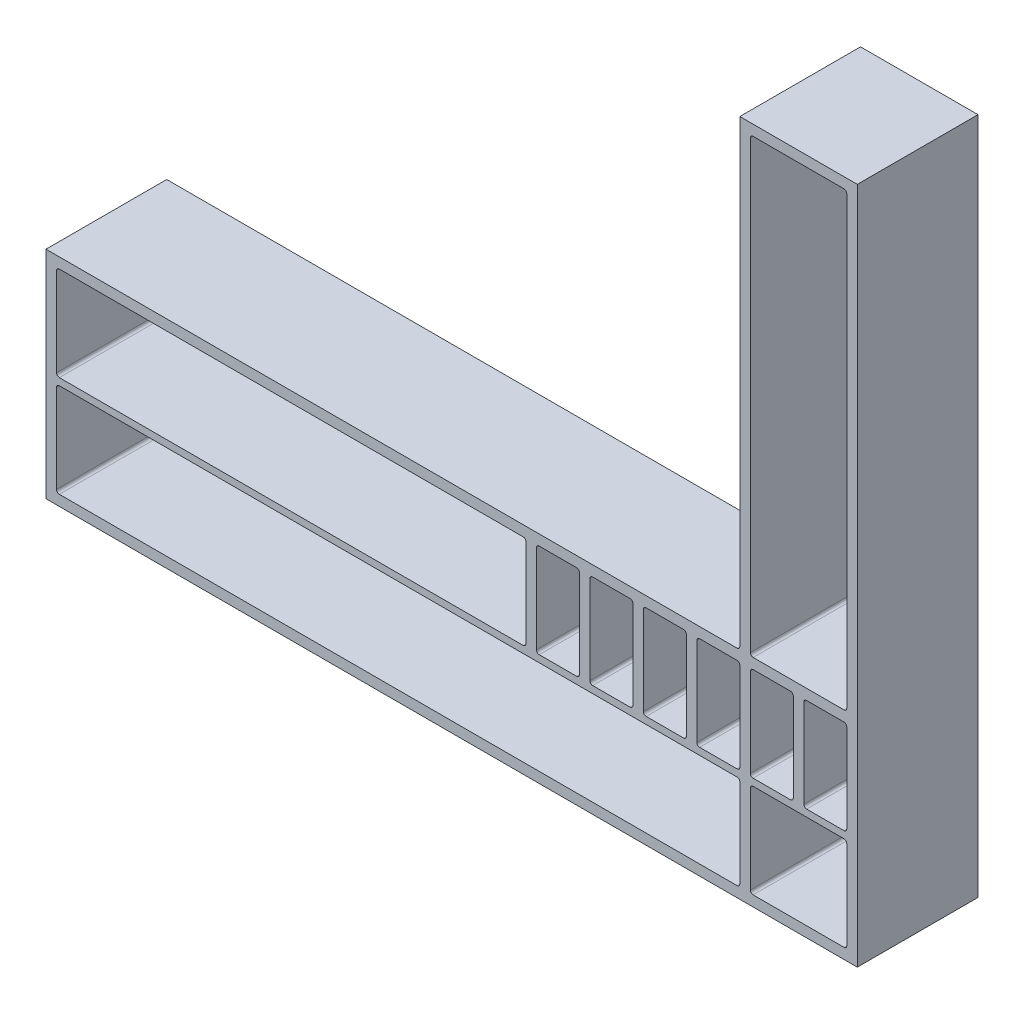
SolidWorks part; units mm, degrees
material "Mahogany"
ref_plane "Front Plane" through (0, 0, 0) normal (0, 0, 1) x (1, 0, 0)
ref_plane "Top Plane" through (0, 0, 0) normal (0, 1, 0) x (1, 0, 0)
ref_plane "Right Plane" through (0, 0, 0) normal (1, 0, 0) x (0, 0, -1)
other "Center of Mass"
sketch "Sketch1" plane through (0, 0, 0) normal (0, 1, 0) x (1, 0, 0)
  line L1 (-1445, -215) -> (1445, -215)
  line L2 (-1445, -215) -> (-1445, 215)
  line L3 (-1445, 215) -> (1445, 215)
  line L4 (1445, -215) -> (1445, 215)
  line L5 (-1445, -215) -> (1445, 215) construction
  line L6 (-1445, 215) -> (1445, -215) construction
  point P1 (0, 0)
  dimension "D1" = 430
  dimension "D2" = 2890
extrude "Boss-Extrude1" add sketch "Sketch1" along normal blind 770
sketch "Sketch2" plane through (0, 0, 215) normal (0, 0, 1) x (1, 0, 0)
  line L0 (0, 770) -> (0, 0) construction
  line L1 (-1445, 770) -> (1445, 770) construction
  line L2 (-1445, 0) -> (1445, 0) construction
  line L3 (-1445, 770) -> (-1445, 0) construction
  line L4 (-1407.5, 37.5) -> (1407.5, 37.5)
  line L5 (-1407.5, 37.5) -> (-1407.5, 732.5)
  line L6 (-1407.5, 732.5) -> (1407.5, 732.5)
  line L7 (1407.5, 37.5) -> (1407.5, 732.5)
  line L8 (-1407.5, 37.5) -> (1407.5, 732.5) construction
  line L9 (-1407.5, 732.5) -> (1407.5, 37.5) construction
  point P6 (0, 385)
  dimension "D1" = 37.5
  dimension "D2" = 37.5
extrude "Cut-Extrude1" cut sketch "Sketch2" against normal blind 397.5
sketch "Sketch3" plane through (0, 0, -182.5) normal (0, 0, 1) x (1, 0, 0)
  line L0 (-1407.5, 372.5) -> (1407.5, 372.5)
  line L1 (1407.5, 37.5) -> (1407.5, 732.5) construction
  line L3 (-1407.5, 37.5) -> (1407.5, 37.5) construction
  line L8 (-1407.5, 397.5) -> (1407.5, 397.5)
  line L10 (-1407.5, 397.5) -> (-1407.5, 372.5)
  line L11 (1407.5, 397.5) -> (1407.5, 372.5)
  line L12 (-1407.5, 732.5) -> (-1407.5, 37.5) construction
  point P5 (-1407.5, 385)
  dimension "D1" = 335
  dimension "D2" = 25
extrude "Boss-Extrude2" add sketch "Sketch3" along normal blind 397.5
sketch "Sketch5" plane through (0, 0, -182.5) normal (0, 0, 1) x (1, 0, 0)
  line L0 (1254.5, 732.5) -> (1254.5, 397.5)
  line L1 (1407.5, 732.5) -> (-1407.5, 732.5) construction
  line L2 (1407.5, 397.5) -> (-1407.5, 397.5) construction
  line L3 (1217, 732.5) -> (1217, 397.5)
  line L4 (1407.5, 397.5) -> (1407.5, 732.5) construction
  line L5 (1217, 732.5) -> (1254.5, 732.5)
  line L6 (1064, 732.5) -> (1064, 397.5)
  line L7 (1407.5, 397.5) -> (-1407.5, 397.5) construction
  line L8 (1064, 397.5) -> (1026.5, 397.5)
  line L9 (1026.5, 397.5) -> (1026.5, 732.5)
  line L10 (1407.5, 732.5) -> (-1407.5, 732.5) construction
  line L11 (1026.5, 732.5) -> (1064, 732.5)
  line L12 (873.5, 397.5) -> (836, 397.5)
  line L13 (836, 397.5) -> (836, 732.5)
  line L14 (836, 732.5) -> (873.5, 732.5)
  line L15 (873.5, 732.5) -> (873.5, 397.5)
  line L16 (683, 397.5) -> (645.5, 397.5)
  line L17 (645.5, 397.5) -> (645.5, 732.5)
  line L18 (645.5, 732.5) -> (683, 732.5)
  line L19 (683, 732.5) -> (683, 397.5)
  line L20 (492.5, 397.5) -> (455, 397.5)
  line L21 (455, 397.5) -> (455, 732.5)
  line L22 (455, 732.5) -> (492.5, 732.5)
  line L23 (492.5, 732.5) -> (492.5, 397.5)
  line L24 (302, 397.5) -> (264.5, 397.5)
  line L25 (264.5, 397.5) -> (264.5, 732.5)
  line L26 (264.5, 732.5) -> (302, 732.5)
  line L27 (302, 732.5) -> (302, 397.5)
  line M18 (-1407.5, 397.5) -> (1407.5, 397.5)
  line M20 (1407.5, 732.5) -> (-1407.5, 732.5)
  dimension "D1" = 37.5
  dimension "D2" = 153
  dimension "D3" = 37.5
  dimension "D4" = 37.5
  dimension "D5" = 153
  dimension "D6" = 153
  dimension "D7" = 37.5
  dimension "D8" = 153
  dimension "D9" = 153
  dimension "D10" = 37.5
  dimension "D11" = 153
  dimension "D12" = 37.5
extrude "Boss-Extrude3" add sketch "Sketch5" along normal blind 397.5 contours L27 L25 M20 M18 | L23 L21 M20 M18 | L19 L17 M20 M18 | L15 L13 M20 M18 | L9 L6 M18 M20 | L3 L0 M20 M18
fillet "Fillet2" radius 10 47 edges at (1407.5, 565, -182.5) (1331, 397.5, -182.5) (1254.5, 565, -182.5) (1331, 732.5, -182.5) (1217, 565, -182.5) (1140.5, 397.5, -182.5) (1064, 565, -182.5) (1140.5, 732.5, -182.5) (1407.5, 732.5, 16.25) (1254.5, 732.5, 16.25) (1254.5, 397.5, 16.25) (1407.5, 397.5, 16.25) (1217, 397.5, 16.25) (1064, 397.5, 16.25) (1064, 732.5, 16.25) (1217, 732.5, 16.25) (1026.5, 732.5, 16.25) (1026.5, 397.5, 16.25) (1026.5, 565, -182.5) (950, 732.5, -182.5) (873.5, 732.5, 16.25) (950, 397.5, -182.5) (873.5, 565, -182.5) (873.5, 397.5, 16.25) (683, 397.5, 16.25) (836, 397.5, 16.25) (836, 732.5, 16.25) (836, 565, -182.5) (683, 565, -182.5) (759.5, 732.5, -182.5) (683, 732.5, 16.25) (645.5, 732.5, 16.25) (492.5, 732.5, 16.25) (492.5, 397.5, 16.25) (645.5, 397.5, 16.25) (645.5, 565, -182.5) (569, 732.5, -182.5) (492.5, 565, -182.5) (569, 397.5, -182.5) (455, 565, -182.5) (378.5, 397.5, -182.5) (302, 565, -182.5) (378.5, 732.5, -182.5) (302, 397.5, 16.25) (455, 397.5, 16.25) (455, 732.5, 16.25) (302, 732.5, 16.25)
sketch "Sketch7" plane through (0, 0, -182.5) normal (0, 0, 1) x (1, 0, 0)
  line L0 (1064, 372.5) -> (1026.5, 372.5)
  line L1 (-1407.5, 372.5) -> (1407.5, 372.5) construction
  line L2 (-1407.5, 372.5) -> (1407.5, 372.5) construction
  line L3 (1026.5, 372.5) -> (1026.5, 37.5)
  line L4 (-1407.5, 37.5) -> (1407.5, 37.5) construction
  line L5 (1026.5, 37.5) -> (1064, 37.5)
  line L6 (1064, 37.5) -> (1064, 372.5)
  line L8 (1064, 722.5) -> (1064, 407.5) construction
  dimension "D1" = 37.5
extrude "Boss-Extrude4" add sketch "Sketch7" along normal blind 397.5
fillet "Fillet3" radius 10 8 edges at (1235.75, 372.5, -182.5) (1407.5, 205, -182.5) (1235.75, 37.5, -182.5) (1064, 205, -182.5) (1064, 372.5, 16.25) (1407.5, 372.5, 16.25) (1407.5, 37.5, 16.25) (1064, 37.5, 16.25)
sketch "Sketch9" plane through (0, 770, 0) normal (0, 1, 0) x (1, 0, 0)
  line L0 (1026.5, 215) -> (1026.5, -215)
  line L1 (1445, 215) -> (-1445, 215) construction
  line L2 (-1445, -215) -> (1445, -215) construction
  line L3 (1445, -215) -> (1445, 215) construction
  line L4 (1407.5, -215) -> (1445, -215)
  line L5 (1445, -215) -> (1445, 215)
  line L6 (1445, 215) -> (1407.5, 215)
  line L7 (1407.5, 177.5) -> (1407.5, -177.5)
  line L8 (1407.5, -215) -> (1026.5, -215)
  line L10 (1064, -177.5) -> (1064, -215)
  line L11 (1407.5, 215) -> (1026.5, 215)
  line L12 (1064, 177.5) -> (1407.5, 177.5)
  line L13 (1064, 177.5) -> (1064, -177.5)
  line L14 (1026.5, 215) -> (1445, 215)
  line L15 (1026.5, -215) -> (1445, -215)
  line L16 (1407.5, -177.5) -> (1407.5, -215)
  line M9 (1445, -215) -> (1445, 215)
  line M10 (1445, 215) -> (-1445, 215)
  line M12 (-1445, -215) -> (1445, -215)
  dimension "D2" = 37.5
  dimension "D1" = 418.5
  dimension "D3" = 37.5
  dimension "D4" = 37.5
extrude "Boss-Extrude5" add sketch "Sketch9" along normal blind 1645 contours L7 L16 L0 L10 L13 L12 M12 M9 M10
sketch "Sketch10" plane through (0, 2415, 0) normal (0, 1, 0) x (1, 0, 0)
  line L0 (1064, -215) -> (1407.5, -215)
  line L1 (1407.5, -215) -> (1407.5, 177.5)
  line L2 (1407.5, 177.5) -> (1064, 177.5)
  line L3 (1064, 177.5) -> (1064, -215)
extrude "Boss-Extrude6" add sketch "Sketch10" against normal blind 37.5
fillet "Fillet4" radius 10 25 edges at (1407.5, 1573.75, -177.5) (1235.75, 770, -177.5) (1064, 1573.75, -177.5) (1235.75, 2377.5, -177.5) (-190.5, 37.5, -182.5) (-1407.5, 205, -182.5) (-190.5, 372.5, -182.5) (1026.5, 205, -182.5) (-1407.5, 565, -182.5) (-571.5, 732.5, -182.5) (264.5, 565, -182.5) (-571.5, 397.5, -182.5) (-1407.5, 37.5, 16.25) (1026.5, 37.5, 16.25) (1026.5, 372.5, 16.25) (264.5, 732.5, 16.25) (-1407.5, 372.5, 16.25) (-1407.5, 732.5, 16.25) (1064, 2377.5, 18.75) (1407.5, 2377.5, 18.75) (1407.5, 770, 18.75) (1064, 770, 18.75) (1026.5, 770, 0) (264.5, 397.5, 16.25) (-1407.5, 397.5, 16.25)
